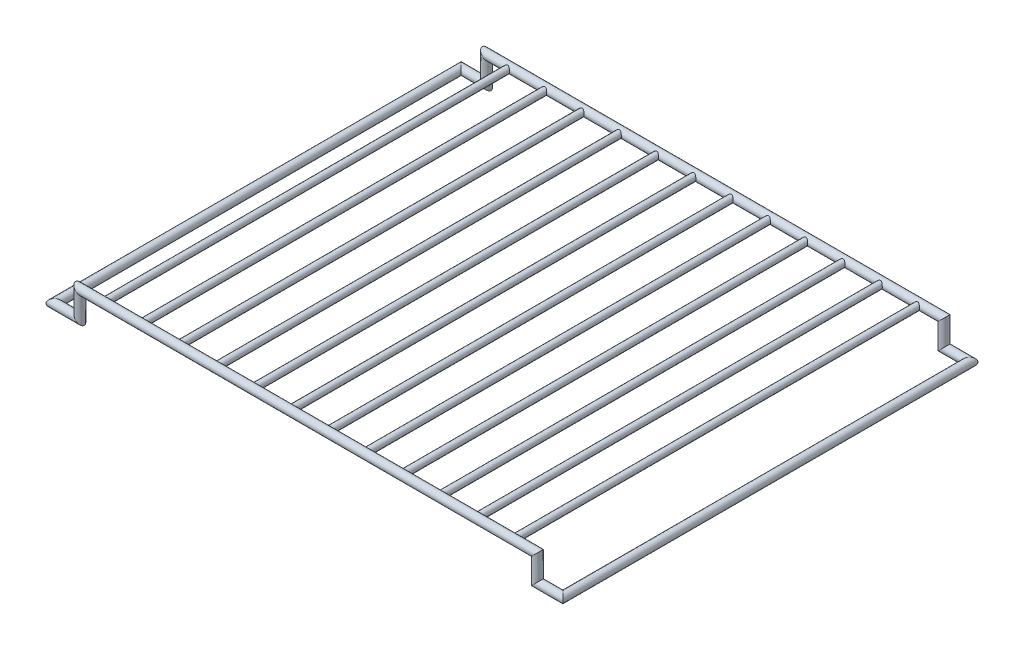
SolidWorks part; units mm, degrees
ref_plane "Front Plane" through (0, 0, 0) normal (0, 0, 1) x (1, 0, 0)
ref_plane "Top Plane" through (0, 0, 0) normal (0, 1, 0) x (1, 0, 0)
ref_plane "Right Plane" through (0, 0, 0) normal (1, 0, 0) x (0, 0, -1)
sketch3d "3DSketch2"
  line L0 (0, 0, 0) -> (135, 0, 0)
  line L1 (135, 0, 0) -> (135, -15, 0)
  line L2 (135, -15, 0) -> (150, -15, 0)
  line L3 (150, -15, 0) -> (150, -15, -240)
  line L4 (150, -15, -240) -> (135, -15, -240)
  line L5 (135, -15, -240) -> (135, 0, -240)
  line L6 (135, 0, -240) -> (0, 0, -240)
  point P9 (0, 0, 0)
  point P10 (0, 0, 0)
  point P11 (0, 0, 0)
  dimension "D1" = 135
  dimension "D2" = 15
  dimension "D3" = 240
  dimension "D4" = 15
  dimension "D5" = 135
  dimension "D6" = 15
  dimension "D7" = 15
sketch "Sketch1" plane through (0, 0, 0) normal (1, 0, 0) x (0, 0, -1)
  circle A0 centre (0, 0) radius 2.5
  dimension "D1" = 5
sweep "Sweep1" add profiles "Sketch1" path "3DSketch2"
sketch "Sketch2" plane through (0, 0, 0) normal (0, 0, 1) x (1, 0, 0)
  circle A0 centre (11, 0) radius 2
  dimension "D1" = 4
  dimension "D2" = 11
extrude "Boss-Extrude1" add sketch "Sketch2" against normal up to surface (237.5 mm away)
pattern_linear "LPattern1" count 6 spacing 22 along (1, 0, 0) of "Boss-Extrude1"
mirror "Mirror1" about plane through (0, 0, 0) normal (1, 0, 0) of "Boss-Extrude1", "LPattern1", "Sweep1"
